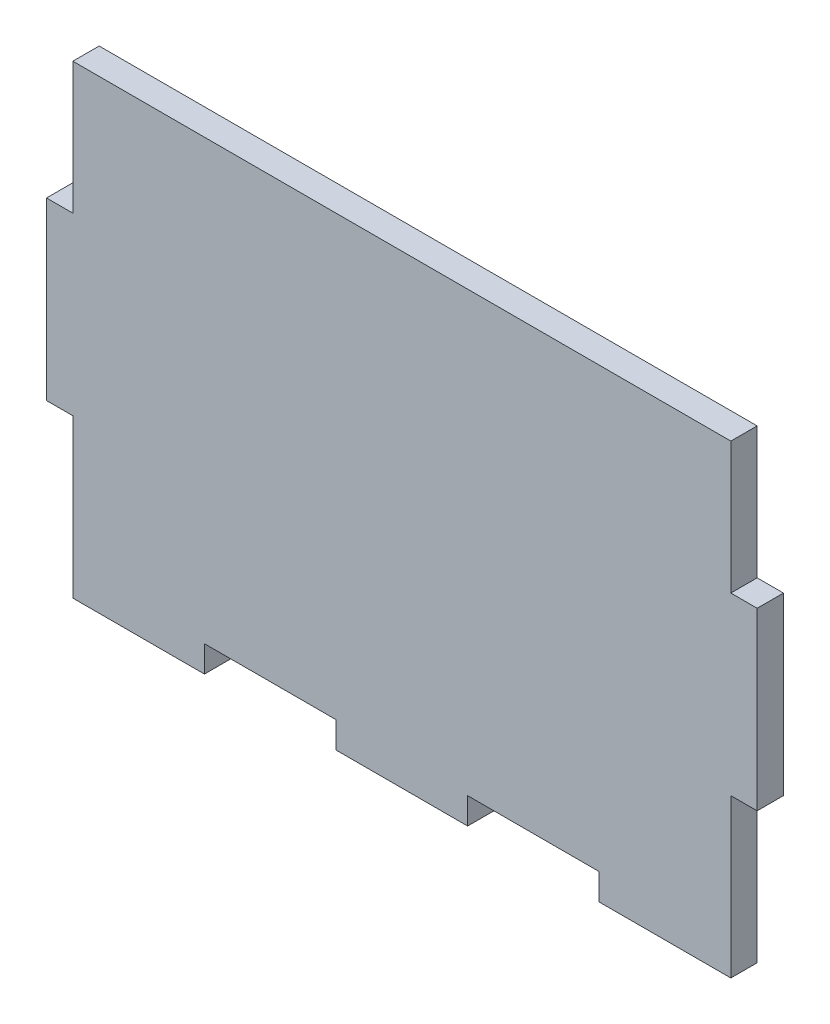
SolidWorks part; units mm, degrees
ref_plane "Plano frontal" through (0, 0, 0) normal (0, 0, 1) x (1, 0, 0)
ref_plane "Plano superior" through (0, 0, 0) normal (0, 1, 0) x (1, 0, 0)
ref_plane "Plano direito" through (0, 0, 0) normal (1, 0, 0) x (0, 0, -1)
sketch "Esboço1" plane through (0, 0, 0) normal (0, 0, 1) x (1, 0, 0)
  line L1 (75, 50) -> (-75, 50)
  line L2 (75, 50) -> (75, -50)
  line L3 (75, -50) -> (-75, -50)
  line L4 (-75, 50) -> (-75, -50)
  line L5 (75, 50) -> (-75, -50) construction
  line L6 (75, -50) -> (-75, 50) construction
  point P0 (0, 0)
  dimension "D1" = 100
  dimension "D2" = 150
extrude "Ressalto-extrusão3" add sketch "Esboço1" along normal blind 6
sketch "Esboço3" plane through (0, -50, 0) normal (0, -1, 0) x (1, 0, 0)
  line L0 (-75, 0) -> (75, 0) construction
  line L1 (-75, 6) -> (-45, 6)
  line L2 (-75, 6) -> (-75, 0)
  line L3 (-75, 0) -> (-45, 0)
  line L4 (-45, 6) -> (-45, 0)
  line L5 (-75, 6) -> (75, 6) construction
  line L6 (-15, 6) -> (15, 6)
  line L7 (-15, 6) -> (-15, 0)
  line L8 (-15, 0) -> (15, 0)
  line L9 (15, 6) -> (15, 0)
  line L11 (75, 6) -> (45, 6)
  line L12 (75, 6) -> (75, 0)
  line L13 (75, 0) -> (45, 0)
  line L14 (45, 6) -> (45, 0)
  dimension "D1" = 30
  dimension "D2" = 30
  dimension "D3" = 30
  dimension "D4" = 30
  dimension "D5" = 30
extrude "Ressalto-extrusão5" add sketch "Esboço3" along normal blind 6
sketch "Esboço4" plane through (75, 0, 0) normal (1, 0, 0) x (0, 0, -1)
  line L10 (-6, -56) -> (-6, 50) construction
  line L15 (-6, 20) -> (0, 20)
  line L16 (-6, 20) -> (-6, -20)
  line L17 (-6, -20) -> (0, -20)
  line L18 (0, 20) -> (0, -20)
  line L19 (0, -56) -> (0, 50) construction
  dimension "D1" = 40
  dimension "D2" = 36
extrude "Ressalto-extrusão6" add sketch "Esboço4" along normal blind 6
sketch "Esboço5" plane through (-75, 0, 0) normal (-1, 0, 0) x (0, 0, 1)
  line L0 (6, 50) -> (6, -56) construction
  line L10 (0, -20) -> (6, -20)
  line L11 (0, -20) -> (0, 20)
  line L12 (0, 20) -> (6, 20)
  line L13 (6, -20) -> (6, 20)
  dimension "D1" = 40
  dimension "D2" = 36
extrude "Ressalto-extrusão7" add sketch "Esboço5" along normal blind 6
